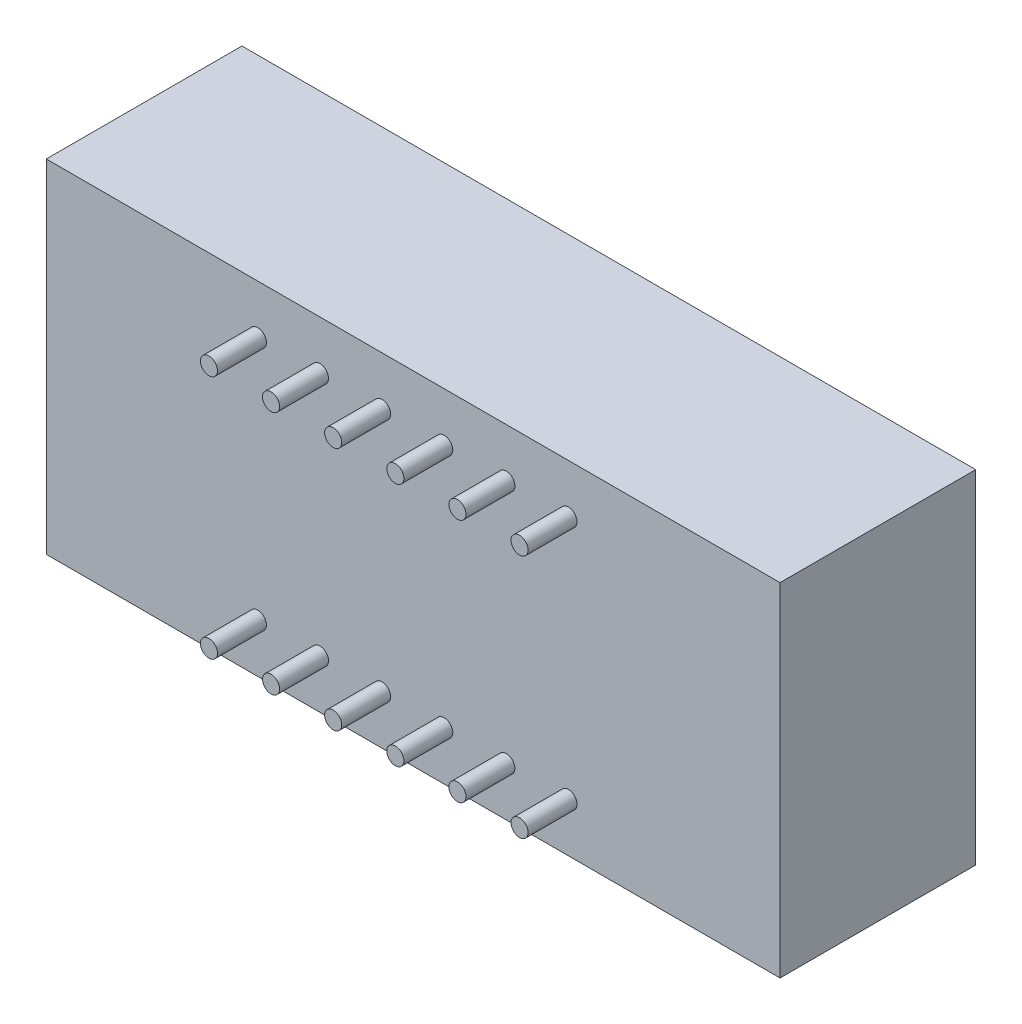
SolidWorks part; units mm, degrees
ref_plane "前视基准面" through (0, 0, 0) normal (0, 0, 1) x (1, 0, 0)
ref_plane "上视基准面" through (0, 0, 0) normal (0, 1, 0) x (1, 0, 0)
ref_plane "右视基准面" through (0, 0, 0) normal (1, 0, 0) x (0, 0, -1)
sketch "草图1" plane through (0, 0, 0) normal (0, 0, 1) x (1, 0, 0)
  line L1 (0, 0) -> (30, 0)
  line L2 (0, 0) -> (0, 14)
  line L3 (0, 14) -> (30, 14)
  line L4 (30, 0) -> (30, 14)
  dimension "D1" = 30
  dimension "D2" = 14
extrude "凸台-拉伸1" add sketch "草图1" along normal blind 8
sketch "草图2" plane through (0, 0, 8) normal (0, 0, 1) x (1, 0, 0)
  line L0 (0, 7) -> (30, 7) construction
  line L1 (0, 14) -> (0, 0) construction
  line L2 (30, 0) -> (30, 14) construction
  line L3 (15, 14) -> (15, 0) construction
  line L4 (30, 14) -> (0, 14) construction
  line L5 (0, 0) -> (30, 0) construction
  circle A0 centre (13.73, 12) radius 0.35
  circle A1 centre (16.27, 12) radius 0.35
  circle A2 centre (18.81, 12) radius 0.35
  circle A3 centre (21.35, 12) radius 0.35
  circle A4 centre (13.73, 2) radius 0.35
  circle A5 centre (16.27, 2) radius 0.35
  circle A6 centre (18.81, 2) radius 0.35
  circle A7 centre (21.35, 2) radius 0.35
  circle A8 centre (11.19, 12) radius 0.35
  circle A9 centre (8.65, 12) radius 0.35
  circle A10 centre (13.73, 2) radius 0.35
  circle A11 centre (11.19, 2) radius 0.35
  circle A12 centre (8.65, 2) radius 0.35
  dimension "D1" = 0.7
  dimension "D2" = 2.54
  dimension "D3" = 10
  dimension "D4" = 4
  dimension "D5" = 2
  dimension "D6" = 3
  dimension "D7" = 2
extrude "凸台-拉伸2" add sketch "草图2" along normal blind 2 contours A9 | A8 | A0 | A1 | A2 | A3 | A12 | A11 | A4 | A5 | A6 | A7
